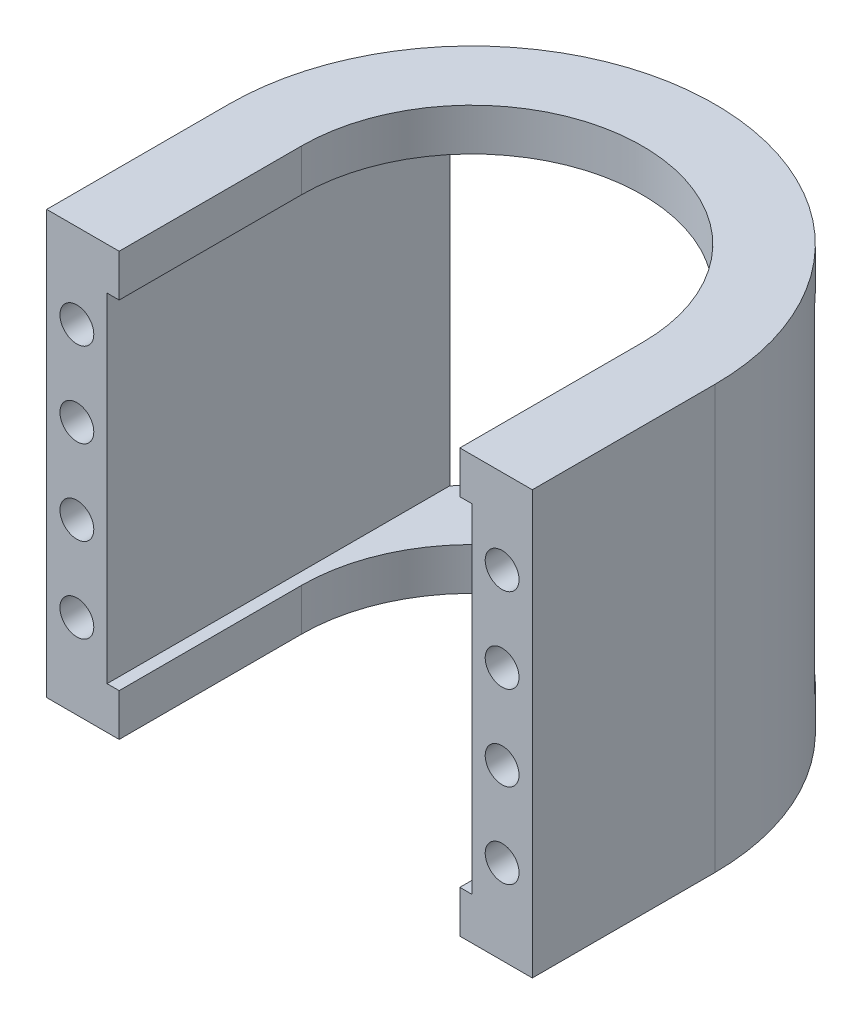
SolidWorks part; units mm, degrees
ref_plane "Front Plane" through (0, 0, 0) normal (0, 0, 1) x (1, 0, 0)
ref_plane "Top Plane" through (0, 0, 0) normal (0, 1, 0) x (1, 0, 0)
ref_plane "Right Plane" through (0, 0, 0) normal (1, 0, 0) x (0, 0, -1)
sketch "Sketch1" plane through (0, 0, 0) normal (0, 1, 0) x (1, 0, 0)
  line L2 (15.1, 0) -> (15.1, -15.1)
  line L10 (-15.1, 0) -> (-15.1, -15.1)
  line L13 (-20.1, 0) -> (-20.1, -10.1) construction
  line L14 (20.1, 0) -> (20.1, -10.1) construction
  line L15 (-15.1, -15.1) -> (-35.1, -15.1) construction
  line L16 (15.1, -15.1) -> (35.1, -15.1) construction
  line L19 (-15.1, -15.1) -> (-20.1, -15.1)
  line L20 (-20.1, 0) -> (-20.1, -15.1)
  line L22 (0, 25.9847) -> (0, -35.8845) construction
  line L24 (15.1, -15.1) -> (20.1, -15.1)
  line L27 (20.1, 0) -> (20.1, -15.1)
  line L29 (-20.1, -10.1) -> (-35.1, -10.1) construction
  line L30 (20.1, -10.1) -> (35.1, -10.1) construction
  arc A0 (15.1, 0) -> (-15.1, 0) centre (0, 0) ccw
  arc A9 (20.1, 0) -> (-20.1, 0) centre (0, 0) ccw
  dimension "D1" = 15.1
  dimension "D2" = 15.1
  dimension "D3" = 15.1
  dimension "D4" = 5
extrude "Boss-Extrude1" add sketch "Sketch1" along normal blind 35
sketch "Sketch2" plane through (0, 0, 15.1) normal (0, 0, 1) x (1, 0, 0)
  line L0 (15.1, 35) -> (-15.1, 35) construction
  line L1 (-15.1, 31.5) -> (15.1, 31.5)
  line L2 (-15.1, 31.5) -> (-15.1, 3.5)
  line L3 (-15.1, 3.5) -> (15.1, 3.5)
  line L4 (15.1, 31.5) -> (15.1, 3.5)
  line L5 (-15.1, 35) -> (-15.1, 0) construction
  line L9 (0, 35) -> (0, 0) construction
  dimension "D1" = 28
  dimension "D2" = 30.2
  dimension "D3" = 3.5
  dimension "D4" = 0
extrude "Cut-Extrude1" cut sketch "Sketch2" against normal through all
sketch "Sketch3" plane through (0, 35, 0) normal (0, 1, 0) x (1, 0, 0)
  line L0 (-15.1, 0) -> (-15.1, -15.1)
  line L1 (15.1, 0) -> (15.1, -15.1)
  line L2 (-14.1, -15.1) -> (-15.1, -15.1)
  line L3 (14.1, -15.1) -> (15.1, -15.1)
  line L4 (14.1, 0) -> (14.1, -15.1)
  line L5 (-14.1, 0) -> (-14.1, -15.1)
  arc A0 (-15.1, 0) -> (15.1, 0) centre (0, 0) cw
  arc A1 (15.1, 0) -> (-15.1, 0) centre (0, 0) ccw construction
  arc A3 (-14.1, 0) -> (14.1, 0) centre (0, 0) cw
  dimension "D1" = 1
extrude "Boss-Extrude2" add sketch "Sketch3" against normal up to surface (3.5 mm away) up to face at (0, 31.5, -12.1166)
sketch "Sketch4" plane through (0, 0, 0) normal (0, -1, 0) x (-1, 0, 0)
  line L0 (15.1, 0) -> (15.1, -15.1)
  line L1 (15.1, -15.1) -> (14.1, -15.1)
  line L2 (14.1, -15.1) -> (14.1, 0)
  line L3 (-14.1, 0) -> (-14.1, -15.1)
  line L4 (-14.1, -15.1) -> (-15.1, -15.1)
  line L5 (-15.1, -15.1) -> (-15.1, 0)
  arc A0 (15.1, 0) -> (-15.1, 0) centre (0, 0) ccw
  arc A1 (14.1, 0) -> (-14.1, 0) centre (0, 0) ccw
  arc A2 (14.1, 0) -> (-14.1, 0) centre (0, 0) ccw construction
extrude "Boss-Extrude3" add sketch "Sketch4" against normal up to surface (3.5 mm away) up to face at (0, 3.5, -12.1166)
sketch "Sketch6" plane through (0, 0, 15.1) normal (0, 0, 1) x (1, 0, 0)
  line L0 (0, 35) -> (0, 0) construction
  line L1 (14.1, 35) -> (-14.1, 35) construction
  line L2 (-14.1, 0) -> (14.1, 0) construction
  line L3 (-20.1, 31.5) -> (-15.1, 31.5) construction
  line L4 (-20.1, 35) -> (-20.1, 0) construction
  line L5 (-17.6, 31.5) -> (-17.6, 0) construction
  line L6 (-20.1, 0) -> (-14.1, 0) construction
  line L7 (-20.1, 35) -> (-14.1, 35) construction
  circle A0 centre (-17.6, 28) radius 1.4
  circle A1 centre (17.6, 28) radius 1.4
  circle A2 centre (17.6, 21) radius 1.4
  circle A3 centre (17.6, 14) radius 1.4
  circle A4 centre (17.6, 7) radius 1.4
  circle A5 centre (-17.6, 21) radius 1.4
  circle A6 centre (-17.6, 14) radius 1.4
  circle A7 centre (-17.6, 7) radius 1.4
  dimension "D1" = 7
  dimension "D2" = 2.8
  dimension "D3" = 2
  dimension "D4" = 4
extrude "Cut-Extrude3" cut sketch "Sketch6" against normal blind 10 contours A0 | A5 | A6 | A7 | A1 | A2 | A3 | A4
